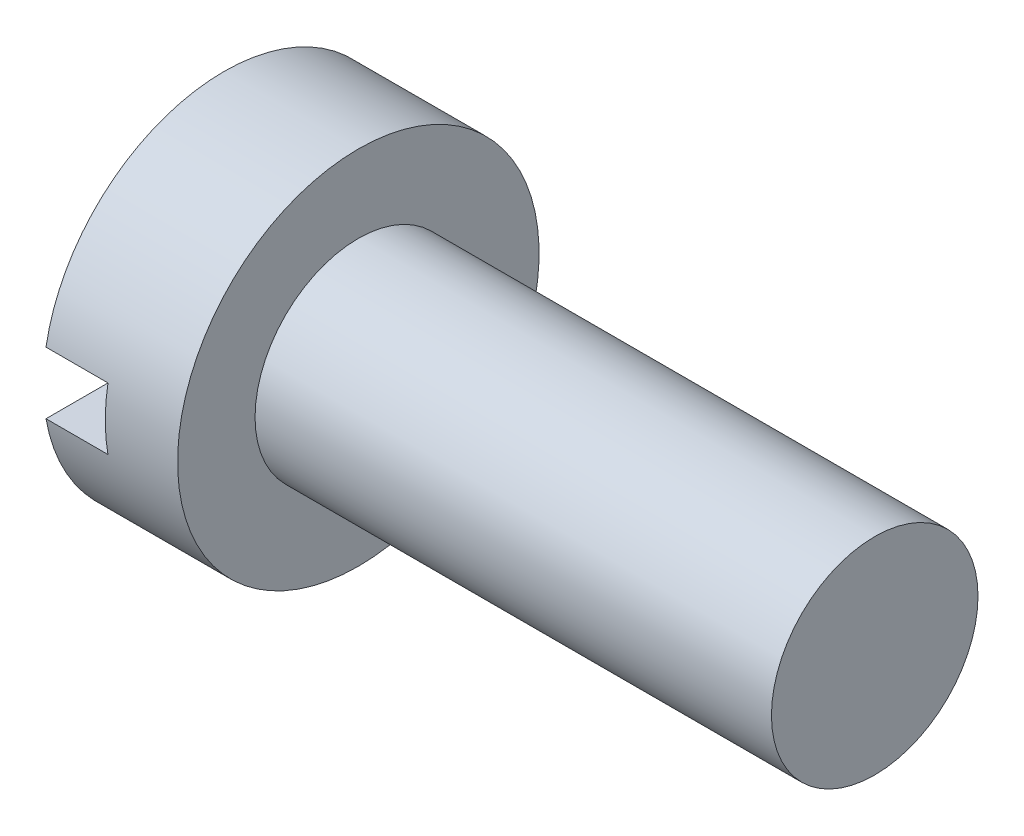
SolidWorks part; units mm, degrees
material "Plain Carbon Steel"
ref_plane "Front Plane" through (0, 0, 0) normal (0, 0, 1) x (1, 0, 0)
ref_plane "Top Plane" through (0, 0, 0) normal (0, 1, 0) x (1, 0, 0)
ref_plane "Right Plane" through (0, 0, 0) normal (1, 0, 0) x (0, 0, -1)
sketch "Sketch1" plane through (0, 0, 0) normal (0, 0, 1) x (1, 0, 0)
  line L0 (0, 0) -> (0, 3.5)
  line L1 (0, 3.5) -> (2.6, 3.5)
  line L2 (2.6, 3.5) -> (2.6, 2)
  line L3 (2.6, 2) -> (12.6, 2)
  line L4 (12.6, 2) -> (12.6, 0)
  line L5 (12.6, 0) -> (0, 0) construction
  line L6 (0, 0) -> (12.6, 0)
  dimension "D1" = 4
  dimension "D2" = 10
  dimension "D3" = 7
  dimension "D4" = 2.6
revolve "Revolve1" add sketch "Sketch1" angle 360 about L5
sketch "Sketch2" plane through (0, 0, 0) normal (-1, 0, 0) x (0, 0, 1)
  line L0 (3.5, 0) -> (-3.5, 0) construction
  line L1 (-3.5, 0.6) -> (3.5, 0.6)
  line L2 (-3.5, 0.6) -> (-3.5, -0.6)
  line L3 (-3.5, -0.6) -> (3.5, -0.6)
  line L4 (3.5, 0.6) -> (3.5, -0.6)
  circle A0 centre (0, 0) radius 3.5 construction
  dimension "D1" = 1.2
extrude "Cut-Extrude1" cut sketch "Sketch2" against normal blind 1.2
